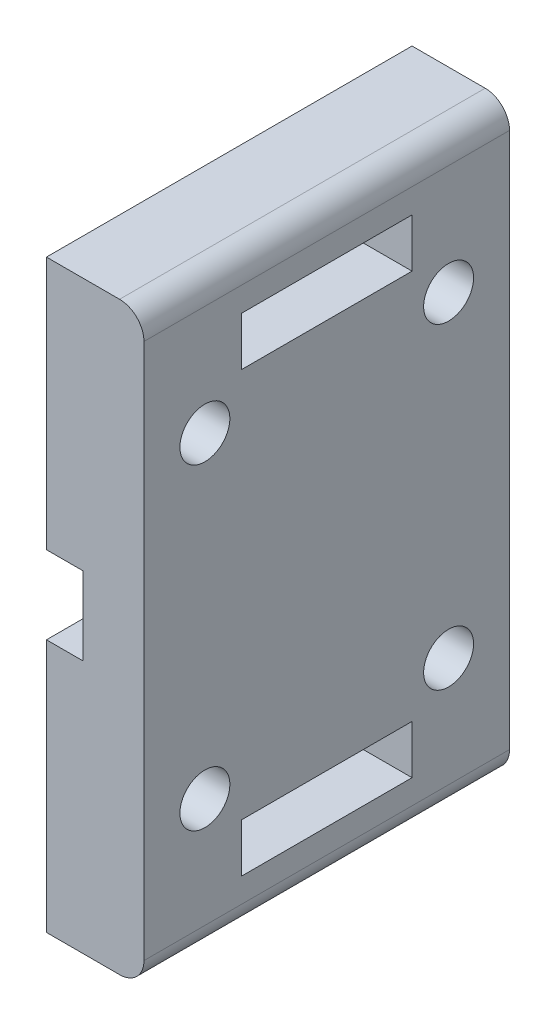
SolidWorks part; units mm, degrees
ref_plane "Front Plane" through (0, 0, 0) normal (0, 0, 1) x (1, 0, 0)
ref_plane "Top Plane" through (0, 0, 0) normal (0, 1, 0) x (1, 0, 0)
ref_plane "Right Plane" through (0, 0, 0) normal (1, 0, 0) x (0, 0, -1)
sketch "Sketch1" plane through (0, 0, -7.5) normal (-1, 0, 0) x (0, 0, 1)
  line L5 (-7.5, -12) -> (7.5, -12)
  line L6 (-7.5, -12) -> (-7.5, 12)
  line L7 (-7.5, 12) -> (7.5, 12)
  line L8 (7.5, -12) -> (7.5, 12)
  line L9 (-7.5, -12) -> (7.5, 12) construction
  line L10 (-7.5, 12) -> (7.5, -12) construction
  dimension "D1" = 15
  dimension "D2" = 24
extrude "Boss-Extrude1" add sketch "Sketch1" along normal blind 4
sketch "Sketch2" plane through (-4, 0, 0) normal (-1, 0, 0) x (0, 0, 1)
  circle A0 centre (-7.5, 0) radius 5.25
  dimension "D1" = 10.5
extrude "Cut-Extrude1" cut sketch "Sketch2" against normal blind 1.5
sketch "Sketch3" plane through (5, 0, 0) normal (0, 0, 1) x (1, 0, 0)
  line L16 (-9, 1.6) -> (-7.5, 1.6)
  line L17 (-9, 1.6) -> (-9, -1.6)
  line L22 (-9, -1.6) -> (-7.5, -1.6)
  line L23 (-7.5, 1.6) -> (-7.5, -1.6)
extrude "Cut-Extrude2" cut sketch "Sketch3" against normal up to next
sketch "Sketch4" plane through (-2.5, 0, 0) normal (-1, 0, 0) x (0, 0, 1)
  circle A0 centre (-7.5, 0) radius 0.8
  dimension "D1" = 1.6
extrude "Cut-Extrude3" cut sketch "Sketch4" against normal blind 1.2
sketch "Sketch5" plane through (-4, 0, 0) normal (-1, 0, 0) x (0, 0, 1)
  line L0 (-11, 10) -> (-4, 10)
  line L1 (-11, -8) -> (-4, -8)
  line L2 (-11, -8) -> (-11, -10)
  line L3 (-11, -10) -> (-4, -10)
  line L4 (-4, -8) -> (-4, -10)
  line L5 (-11, 10) -> (-11, 8)
  line L6 (-11, 8) -> (-4, 8)
  line L7 (-4, 10) -> (-4, 8)
extrude "Cut-Extrude4" cut sketch "Sketch5" against normal through all
hole_wizard "M2.5x0.45 Tapped Hole1" positions "Sketch6" profile "Sketch7" tap size "M2.5x0.45" standard "JIS"
sketch "Sketch6" plane through (-4, 0, 0) normal (-1, 0, 0) x (0, 0, 1)
  point P0 (-12.5, -6.5)
  point P2 (-12.5, 6.5)
  point P13 (-2.5, 6.5)
  point P15 (-2.5, -6.5)
sketch "Sketch7" plane through (-4, -6.5, -12.5) normal (0, 1, 0) x (0, 0, 1)
  line L0 (0, 0) -> (0, 6.9659)
  line L1 (0, 6.9659) -> (1.025, 6.35)
  line L2 (1.025, 6.35) -> (1.025, 0)
  line L5 (1.025, 0) -> (0, 0)
  line L10 (0, 6.9659) -> (-1.025, 6.35) construction
  line L11 (0, -6.35) -> (0, 107.95) construction
  dimension "Tap Drill Dia." = 2.05
  dimension "Tap Drill Depth" = 6.35
  dimension "Drill Angle" = 118
cosmetic thread "Hole Thread1" parameters "D1"=5, "D2"=2.5
cosmetic thread "Hole Thread2" parameters "D1"=5, "D2"=2.5
cosmetic thread "Hole Thread3" parameters "D1"=5, "D2"=2.5
cosmetic thread "Hole Thread4" parameters "D1"=5, "D2"=2.5
fillet "Fillet1" radius 1 2 edges at (0, -12, -7.5) (0, 12, -7.5)
